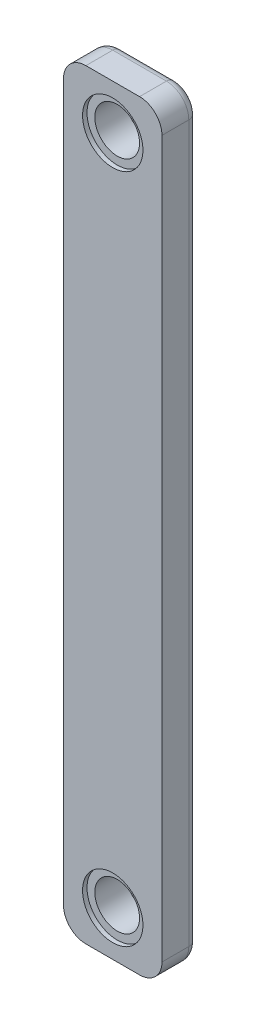
SolidWorks part; units mm, degrees
material "POM Acetal Copolymer"
ref_plane "Front Plane" through (0, 0, 0) normal (0, 0, 1) x (1, 0, 0)
ref_plane "Top Plane" through (0, 0, 0) normal (0, 1, 0) x (1, 0, 0)
ref_plane "Right Plane" through (0, 0, 0) normal (1, 0, 0) x (0, 0, -1)
sketch "Sketch1" plane through (0, 0, 0) normal (0, 0, 1) x (1, 0, 0)
  line L1 (-11, -85) -> (11, -85)
  line L2 (-11, -85) -> (-11, 85)
  line L3 (-11, 85) -> (11, 85)
  line L4 (11, -85) -> (11, 85)
  line L5 (-11, -85) -> (11, 85) construction
  line L6 (-11, 85) -> (11, -85) construction
  point P0 (0, 0)
  dimension "D1" = 22
  dimension "D2" = 170
extrude "Boss-Extrude1" add sketch "Sketch1" along normal mid plane 8
fillet "Fillet1" radius 5 4 edges at (11, -85, 0) (-11, -85, 0) (-11, 85, 0) (11, 85, 0)
fillet "Fillet2" radius 2 8 edges at (9.5355, 83.5355, -4) (0, 85, -4) (-9.5355, 83.5355, -4) (-11, 0, -4) (-9.5355, -83.5355, -4) (0, -85, -4) (9.5355, -83.5355, -4) (11, 0, -4)
sketch "Sketch2" plane through (0, 0, 4) normal (0, 0, 1) x (1, 0, 0)
  circle A0 centre (0, 75) radius 5
  circle A1 centre (0, -75) radius 5
  dimension "D1" = 10
  dimension "D2" = 10
extrude "Cut-Extrude1" cut sketch "Sketch2" against normal through all
sketch "Sketch3" plane through (0, 0, 4) normal (0, 0, 1) x (1, 0, 0)
  circle A0 centre (0, 75) radius 6.75
  circle A1 centre (0, -75) radius 6.75
  dimension "D1" = 13.5
  dimension "D2" = 13.5
extrude "Cut-Extrude2" cut sketch "Sketch3" against normal blind 1
